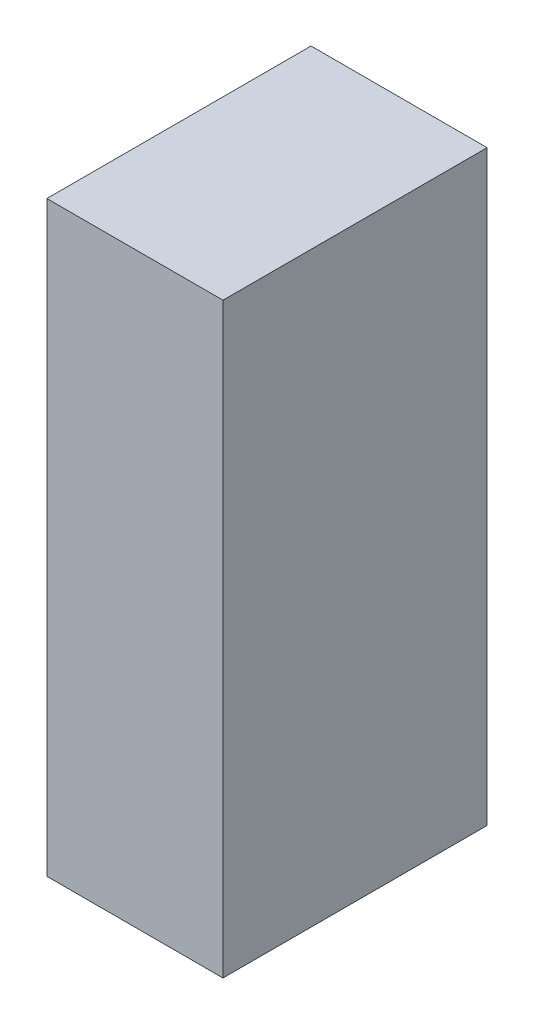
SolidWorks part; units mm, degrees
ref_plane "Front Plane" through (0, 0, 0) normal (0, 0, 1) x (1, 0, 0)
ref_plane "Top Plane" through (0, 0, 0) normal (0, 1, 0) x (1, 0, 0)
ref_plane "Right Plane" through (0, 0, 0) normal (1, 0, 0) x (0, 0, -1)
sketch "Sketch1" plane through (0, 0, 0) normal (0, 0, 1) x (1, 0, 0)
  line L0 (2234.8178, 0) -> (26234.8178, 0)
  line L1 (26234.8178, 0) -> (26234.8178, 80000)
  line L2 (26234.8178, 80000) -> (2234.8178, 80000)
  line L3 (2234.8178, 80000) -> (2234.8178, 0)
  dimension "D1" = 24000
  dimension "D2" = 80000
extrude "Boss-Extrude1" add sketch "Sketch1" along normal blind 36000
sketch "Sketch2" plane through (0, 0, 36000) normal (0, 0, 1) x (1, 0, 0)
  line L0 (26234.8178, 0) -> (42234.8178, 0)
  line L1 (42234.8178, 0) -> (42234.8178, 20000)
  line L2 (42234.8178, 20000) -> (26234.8178, 20000)
  line L3 (26234.8178, 0) -> (26234.8178, 80000) construction
  line L4 (26234.8178, 20000) -> (26234.8178, 0)
  line L5 (2234.8178, 0) -> (2234.8178, 20000)
  line L6 (2234.8178, 0) -> (26234.8178, 0) construction
  line L7 (2234.8178, 80000) -> (2234.8178, 0) construction
  line L8 (2234.8178, 20000) -> (-13765.1822, 20000)
  line L9 (-13765.1822, 20000) -> (-13765.1822, 0)
  line L10 (-13765.1822, 0) -> (2234.8178, 0)
  line L11 (26234.8178, 0) -> (26234.8178, 20000)
  dimension "D1" = 16000
  dimension "D2" = 20000
  dimension "D3" = 20000
  dimension "D4" = 16000
